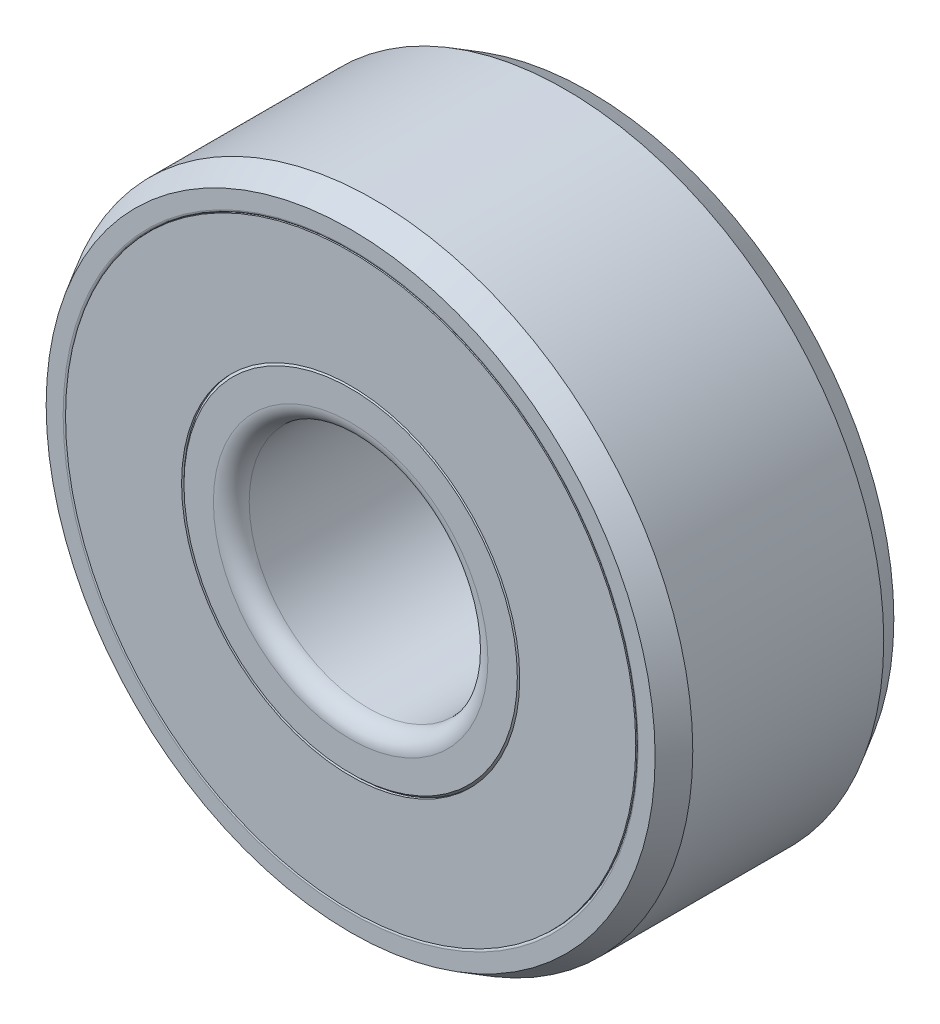
SolidWorks part; units mm, degrees
ref_plane "Front Plane" through (0, 0, 0) normal (0, 0, 1) x (1, 0, 0)
ref_plane "Top Plane" through (0, 0, 0) normal (0, 1, 0) x (1, 0, 0)
ref_plane "Right Plane" through (0, 0, 0) normal (1, 0, 0) x (0, 0, -1)
sketch "Sketch1" plane through (0, 0, 0) normal (0, 0, 1) x (1, 0, 0)
  line L0 (0, 2.75) -> (0, 4) construction
  line L1 (0, 1.5) -> (0, 2.75) construction
  line L2 (0, 4) -> (0, 3.5833) construction
  line L3 (0, 3.5833) -> (0, 3.1667) construction
  line L4 (0, 3.1667) -> (0, 2.75) construction
  circle A0 centre (0, 0) radius 1.5
  circle A1 centre (0, 0) radius 4
  circle A2 centre (0, 0) radius 3.5833 construction
  circle A4 centre (0, 0) radius 2.125 construction
  point P6 (0, 2.125)
  dimension "OD" = 8
  dimension "ID" = 3
sketch "Sketch2" plane through (0, 0, 0) normal (1, 0, 0) x (0, 0, -1)
  line L0 (-1.5, 4) -> (1.5, 4) construction
  line L1 (1.5, 4) -> (1.5, -4) construction
  line L2 (1.5, 0) -> (-1.5, 0) construction
  line L3 (-1.5, 1.5) -> (-1.5, -1.5) construction
  point P2 (0, 4)
  dimension "Width" = 3
  dimension "For Shaft Diameter" = 3
  dimension "For Housing ID" = 8
sketch "Sketch3" plane through (0, 0, 0) normal (1, 0, 0) x (0, 0, -1)
  line L0 (-1.2, -4) -> (1.2, -4)
  line L3 (-1.5, -3.6133) -> (-1.5, -3.8268)
  line L4 (0, -2.125) -> (0, -3.5833) construction
  line L5 (-1.2, -4) -> (-1.5, -3.8268)
  line L6 (-1.275, -1.5) -> (1.275, -1.5)
  line L7 (-0.6944, -3.5833) -> (-0.6944, -3.7222) construction
  line L8 (-1.47, -2.125) -> (-0.6944, -2.125)
  line L9 (-1.5, -2.125) -> (0, -2.125) construction
  line L11 (-1.5, -3.5833) -> (-1.5, -2.125) construction
  line L12 (-1.5, -2.095) -> (-1.5, -1.725)
  line L14 (-1.5, 0) -> (1.5, 0) construction
  line L15 (-1.47, -3.5833) -> (-0.6944, -3.5833)
  line L17 (0, 0) -> (0, -4) construction
  line L18 (-0.6944, -3.7222) -> (-0.6944, -3.8611) construction
  line L19 (1.2, -4) -> (1.5, -3.8268)
  line L20 (0, -3.5833) -> (-1.5, -3.5833) construction
  line L21 (-1.5, 1.5) -> (-1.5, -1.5) construction
  line L22 (-0.6944, -3.8611) -> (-0.6944, -4) construction
  line L30 (-1.5, -2.095) -> (-1.47, -2.125)
  line L31 (1.47, -2.125) -> (0.6944, -2.125)
  line L32 (1.5, -2.095) -> (1.47, -2.125)
  line L33 (1.5, -2.095) -> (1.5, -1.725)
  line L34 (1.47, -3.5833) -> (0.6944, -3.5833)
  line L35 (1.5, -3.6133) -> (1.5, -3.8268)
  line L36 (0, 4) -> (0, -4) construction
  arc A0 (0, -1.8472) -> (0, -3.8611) centre (0, -2.8542) ccw construction
  arc A1 (-0.6944, -2.125) -> (0.6944, -2.125) centre (0, -2.8542) cw
  arc A2 (-0.6944, -3.5833) -> (0.6944, -3.5833) centre (0, -2.8542) ccw
  arc A4 (-1.47, -3.5833) -> (-1.5, -3.6133) centre (-1.47, -3.6133) ccw
  arc A5 (-1.275, -1.5) -> (-1.5, -1.725) centre (-1.275, -1.725) ccw
  arc A6 (1.275, -1.5) -> (1.5, -1.725) centre (1.275, -1.725) cw
  arc A7 (1.47, -3.5833) -> (1.5, -3.6133) centre (1.47, -3.6133) cw
  point P28 (0, -2.8542)
  point P46 (-1.5, -1.5)
  point P54 (0, -1.5)
  dimension "D4" = 0.03
  dimension "D7" = 0.225
  dimension "D5" = 45
  dimension "D6" = 0.03
  dimension "D3" = 0.3
  dimension "D2" = 60
revolve "Revolve1" add sketch "Sketch3" angle 360 about L14
sketch "Sketch4" plane through (0, 0, 0) normal (1, 0, 0) x (0, 0, -1)
  line L0 (-1.47, -3.5833) -> (-0.6944, -3.5833) construction
  line L1 (-1.5, -2.125) -> (-1.1302, -2.125)
  line L2 (-1.5, -2.125) -> (-1.5, -3.5833)
  line L3 (-1.5, -3.5833) -> (-1.1302, -3.5833)
  line L4 (-1.1302, -2.125) -> (-1.1302, -3.5833)
  line L5 (-1.5, -2.095) -> (-1.5, -1.725) construction
  line L6 (-1.5, -2.8542) -> (-1.3767, -2.8542) construction
  line L7 (-1.3767, -2.8542) -> (-1.2535, -2.8542) construction
  line L8 (-1.2535, -2.8542) -> (-1.1302, -2.8542) construction
  line L9 (-1.1302, -2.8542) -> (-1.0069, -2.8542) construction
  line L10 (-1.5, -3.5833) -> (-1.5, -2.125) construction
  line L11 (-1.47, -2.125) -> (-0.6944, -2.125) construction
  arc A1 (0, -1.8472) -> (0, -3.8611) centre (0, -2.8542) ccw construction
revolve "Revolve2" add sketch "Sketch4" angle 360 about L14
sketch "Sketch5" plane through (0, 0, 0) normal (1, 0, 0) x (0, 0, -1)
  line L2 (0, -1.8472) -> (0, -3.8611)
  arc A2 (0, -3.8611) -> (0, -1.8472) centre (0, -2.8542) cw
revolve "Revolve3" add sketch "Sketch5" angle 360 about L17
pattern_circular "CirPattern1" count 7 over 360 about axis through (0, 0, 0) along (0, 0, 1) of bodies 138
equation "\"D4@Sketch3\"=\"Width@Sketch2\"*.01"
equation "\"D6@Sketch3\"=\"Width@Sketch2\"*.01"
equation "\"D7@Sketch3\"=\"Width@Sketch2\"*.075"
equation "\"D3@Sketch3\"=\"Width@Sketch2\"*.1"
